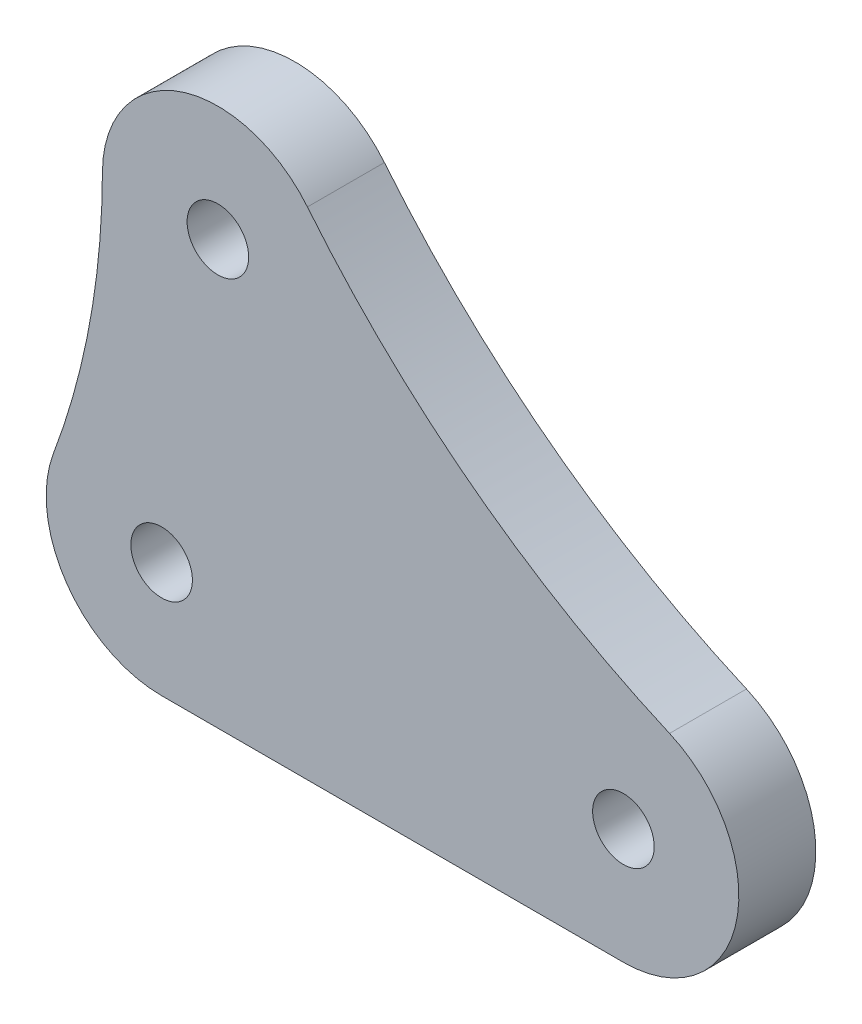
SolidWorks part; units mm, degrees
ref_plane "Piano frontale" through (0, 0, 0) normal (0, 0, 1) x (1, 0, 0)
ref_plane "Piano superiore" through (0, 0, 0) normal (0, 1, 0) x (1, 0, 0)
ref_plane "Piano destro" through (0, 0, 0) normal (1, 0, 0) x (0, 0, -1)
sketch "Schizzo1" plane through (0, 0, 0) normal (0, 0, 1) x (1, 0, 0)
  line L0 (0, -7.5) -> (-30, -7.5)
  circle A0 centre (0, 0) radius 2
  arc A1 (0, -7.5) -> (2.995, 6.8761) centre (0, 0) ccw
  circle A2 centre (-30, 0) radius 2
  arc A3 (-37.0234, 2.6309) -> (-30, -7.5) centre (-30, 0) ccw
  circle A4 centre (-26.3465, 20) radius 2
  arc A5 (-20.5287, 24.7332) -> (-33.8464, 20.0222) centre (-26.3465, 20) ccw
  arc A6 (-37.0234, 2.6309) -> (-33.8464, 20.0222) centre (-83.8462, 20.1702) ccw
  arc A7 (-20.5287, 24.7332) -> (2.995, 6.8761) centre (27.953, 64.1765) ccw
  dimension "D1" = 4
  dimension "D2" = 15
  dimension "D3" = 4
  dimension "D4" = 20
  dimension "D6" = 4
  dimension "D7" = 15
  dimension "D8" = 100
  dimension "D9" = 125
  dimension "D5" = 30
extrude "Estrusione-Estrusione2" add sketch "Schizzo1" along normal blind 5
